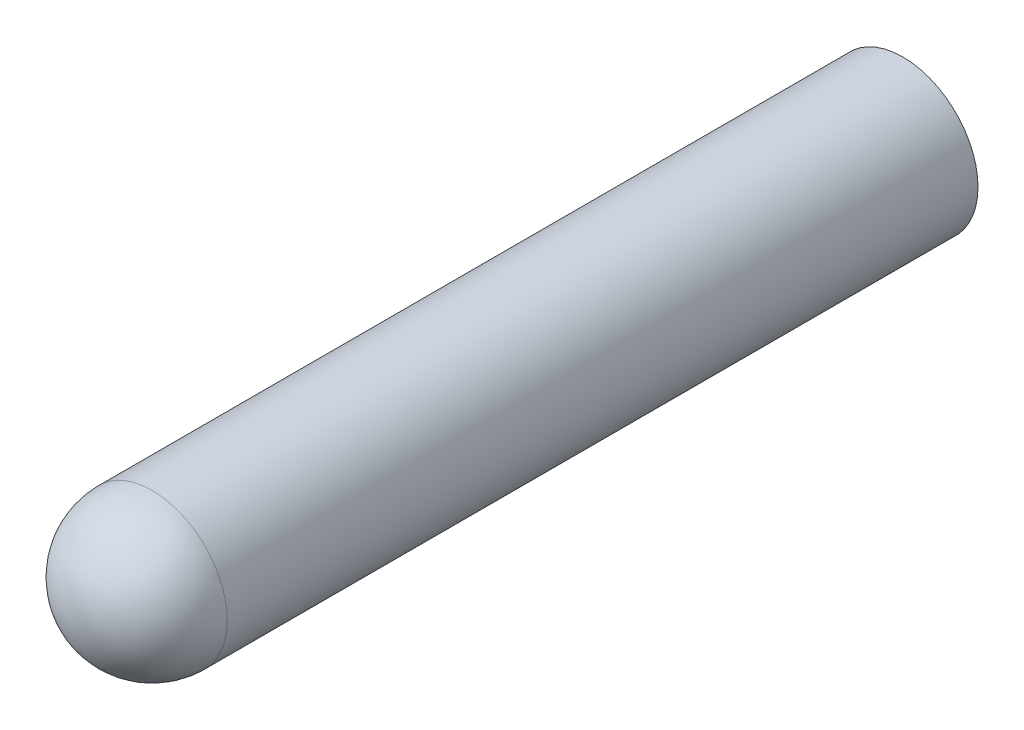
SolidWorks part; units mm, degrees
ref_plane "前视基准面" through (0, 0, 0) normal (0, 0, 1) x (1, 0, 0)
ref_plane "上视基准面" through (0, 0, 0) normal (0, 1, 0) x (1, 0, 0)
ref_plane "右视基准面" through (0, 0, 0) normal (1, 0, 0) x (0, 0, -1)
sketch "草图1" plane through (0, 0, 0) normal (0, 0, 1) x (1, 0, 0)
  circle A0 centre (0, 0) radius 1
  dimension "D1" = 2
extrude "凸台-拉伸1" add sketch "草图1" along normal mid plane 11
fillet "圆角1" radius 1 1 edges at (1, 0, 5.5)
